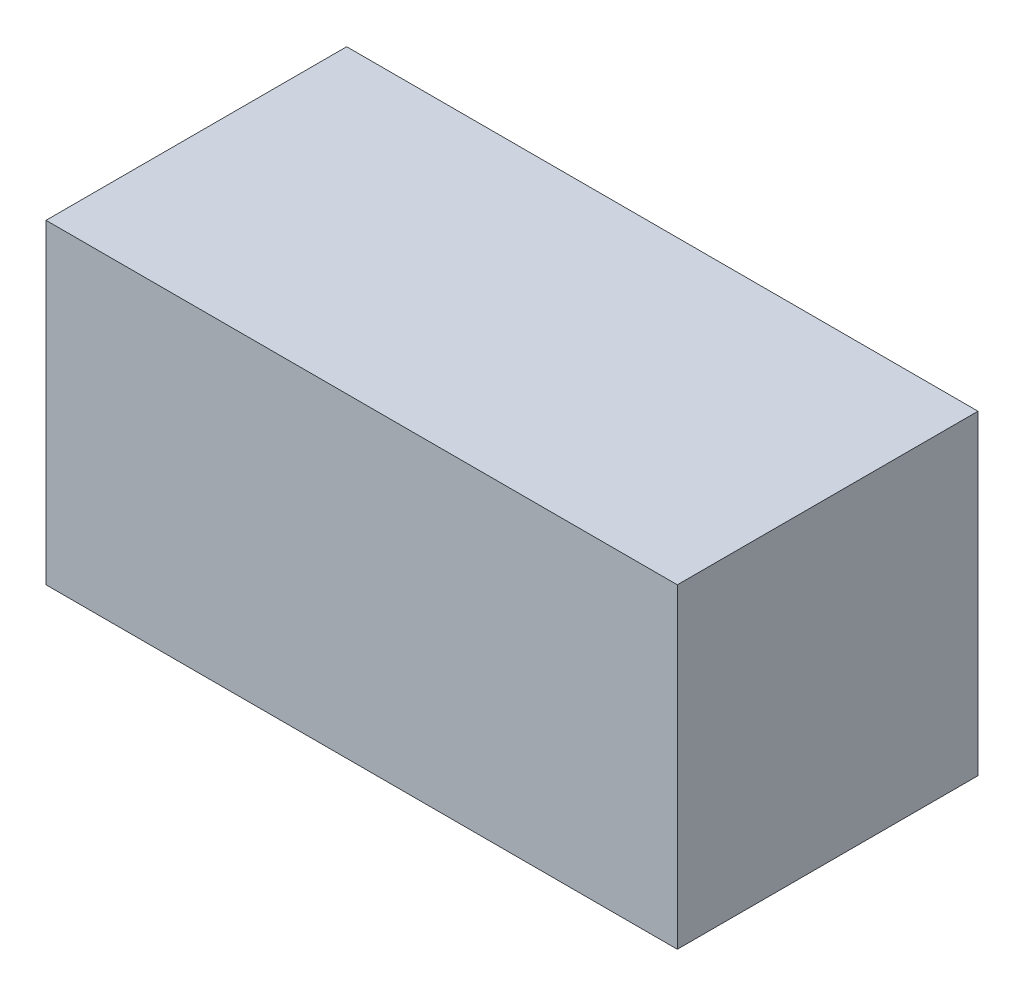
SolidWorks part; units mm, degrees
ref_plane "Front Plane" through (0, 0, 0) normal (0, 0, 1) x (1, 0, 0)
ref_plane "Top Plane" through (0, 0, 0) normal (0, 1, 0) x (1, 0, 0)
ref_plane "Right Plane" through (0, 0, 0) normal (1, 0, 0) x (0, 0, -1)
sketch "Sketch1" plane through (0, 0, 0) normal (0, 0, 1) x (1, 0, 0)
  line L1 (-0.8, 0.4) -> (0.8, 0.4)
  line L2 (-0.8, 0.4) -> (-0.8, -0.4)
  line L3 (-0.8, -0.4) -> (0.8, -0.4)
  line L4 (0.8, 0.4) -> (0.8, -0.4)
  line L5 (-0.8, 0.4) -> (0.8, -0.4) construction
  line L6 (-0.8, -0.4) -> (0.8, 0.4) construction
  point P0 (0, 0)
  dimension "D1" = 0.8
  dimension "D2" = 1.6
extrude "Boss-Extrude1" add sketch "Sketch1" along normal blind 0.762
